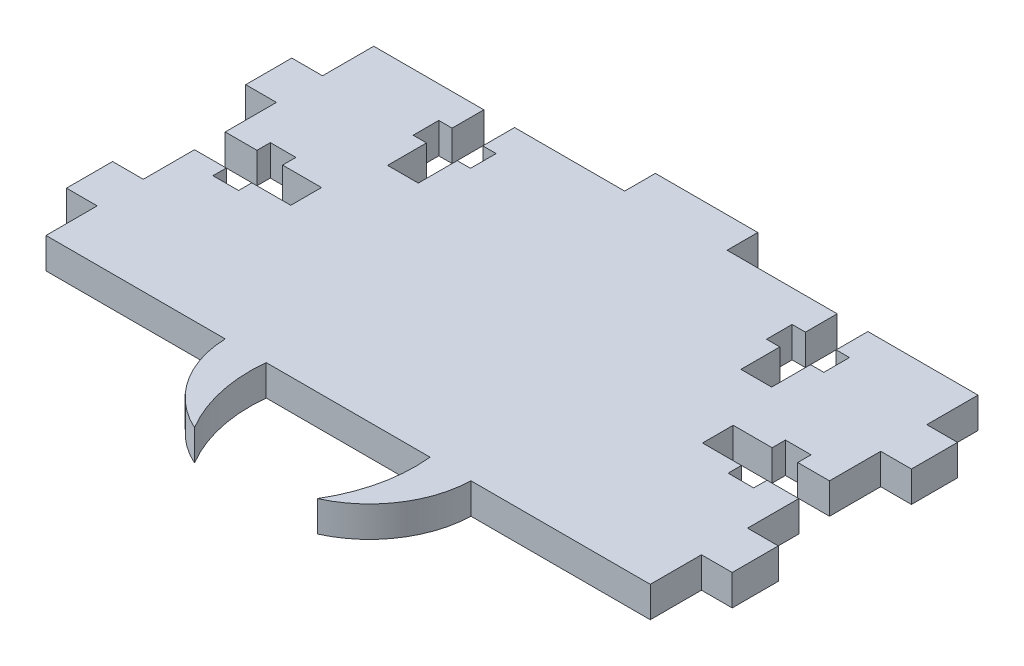
SolidWorks part; units mm, degrees
ref_plane "Front Plane" through (0, 0, 0) normal (0, 0, 1) x (1, 0, 0)
ref_plane "Top Plane" through (0, 0, 0) normal (0, 1, 0) x (1, 0, 0)
ref_plane "Right Plane" through (0, 0, 0) normal (1, 0, 0) x (0, 0, -1)
sketch "Sketch1" plane through (0, 0, 0) normal (0, 1, 0) x (1, 0, 0)
  line L0 (0, 27) -> (3, 27)
  line L1 (0, 0) -> (-17.5, 0)
  line L2 (0, 0) -> (0, 5)
  line L3 (0, 32) -> (-10.75, 32)
  line L4 (-59, 0) -> (-59, 5)
  line L5 (0, 17.5) -> (-3.1, 17.5)
  line L6 (-3.1, 17.5) -> (-3.1, 18.8)
  line L7 (-3.1, 18.8) -> (-5.6, 18.8)
  line L8 (-5.6, 18.8) -> (-5.6, 17.5)
  line L9 (-5.6, 17.5) -> (-9.4, 17.5)
  line L10 (-9.4, 17.5) -> (-9.4, 14.5)
  line L11 (-9.4, 14.5) -> (-5.6, 14.5)
  line L12 (-5.6, 14.5) -> (-5.6, 13.2)
  line L13 (-5.6, 13.2) -> (-3.1, 13.2)
  line L14 (-3.1, 13.2) -> (-3.1, 14.5)
  line L15 (-3.1, 14.5) -> (0, 14.5)
  line L16 (0, 17.5) -> (0, 22.5)
  line L17 (3, 27) -> (3, 22.5)
  line L18 (3, 22.5) -> (0, 22.5)
  line L19 (0, 27) -> (0, 32)
  line L20 (-49.6, 16) -> (-9.4, 16) construction
  line L21 (-29.5, 35) -> (-29.5, 0) construction
  line L22 (3, 9.5) -> (0, 9.5)
  line L23 (0, 5) -> (3, 5)
  line L24 (3, 5) -> (3, 9.5)
  line L25 (0, 9.5) -> (0, 14.5)
  line L26 (-55.9, 13.2) -> (-55.9, 14.5)
  line L27 (-53.4, 14.5) -> (-53.4, 13.2)
  line L28 (-55.9, 17.5) -> (-55.9, 18.8)
  line L29 (-53.4, 18.8) -> (-53.4, 17.5)
  line L30 (-55.9, 18.8) -> (-53.4, 18.8)
  line L31 (-53.4, 13.2) -> (-55.9, 13.2)
  line L32 (-49.6, 17.5) -> (-49.6, 14.5)
  line L33 (-49.6, 14.5) -> (-53.4, 14.5)
  line L34 (-53.4, 17.5) -> (-49.6, 17.5)
  line L35 (-59, 17.5) -> (-55.9, 17.5)
  line L36 (-55.9, 14.5) -> (-59, 14.5)
  line L37 (-59, 5) -> (-62, 5)
  line L38 (-62, 5) -> (-62, 9.5)
  line L39 (-62, 9.5) -> (-59, 9.5)
  line L40 (-59, 27) -> (-62, 27)
  line L41 (-62, 27) -> (-62, 22.5)
  line L42 (-62, 22.5) -> (-59, 22.5)
  line L43 (-59, 17.5) -> (-59, 22.5)
  line L44 (-59, 27) -> (-59, 32)
  line L45 (-59, 9.5) -> (-59, 14.5)
  line L46 (-21.5, 0) -> (-37.5, 0)
  line L47 (-41.5, 0) -> (-59, 0)
  line L48 (-48.25, 32) -> (-48.25, 28.9)
  line L49 (-24.5, 32) -> (-24.5, 35)
  line L50 (-24.5, 35) -> (-34.5, 35)
  line L51 (-34.5, 35) -> (-34.5, 32)
  line L52 (-34.5, 32) -> (-45.25, 32)
  line L53 (-48.25, 28.9) -> (-49.55, 28.9)
  line L54 (-49.55, 28.9) -> (-49.55, 26.4)
  line L55 (-49.55, 26.4) -> (-48.25, 26.4)
  line L56 (-48.25, 26.4) -> (-48.25, 22.6)
  line L57 (-48.25, 22.6) -> (-45.25, 22.6)
  line L58 (-45.25, 22.6) -> (-45.25, 26.4)
  line L59 (-45.25, 26.4) -> (-43.95, 26.4)
  line L60 (-43.95, 26.4) -> (-43.95, 28.9)
  line L61 (-43.95, 28.9) -> (-45.25, 28.9)
  line L62 (-45.25, 28.9) -> (-45.25, 32)
  line L63 (-48.25, 32) -> (-59, 32)
  line L64 (-10.75, 22.6) -> (-13.75, 22.6)
  line L65 (-10.75, 26.4) -> (-10.75, 22.6)
  line L66 (-15.05, 28.9) -> (-13.75, 28.9)
  line L67 (-10.75, 28.9) -> (-9.45, 28.9)
  line L68 (-9.45, 26.4) -> (-10.75, 26.4)
  line L69 (-9.45, 28.9) -> (-9.45, 26.4)
  line L70 (-10.75, 32) -> (-10.75, 28.9)
  line L71 (-13.75, 28.9) -> (-13.75, 32)
  line L72 (-15.05, 26.4) -> (-15.05, 28.9)
  line L73 (-13.75, 26.4) -> (-15.05, 26.4)
  line L74 (-13.75, 22.6) -> (-13.75, 26.4)
  line L75 (-13.75, 32) -> (-24.5, 32)
  arc A0 (-21.5, 0) -> (-23.5, -9) centre (-35.9728, -1.506) cw
  arc A1 (-17.5, 0) -> (-23.5, -9) centre (-27.7534, 0.3356) cw
  arc A2 (-37.5, 0) -> (-35.5, -9) centre (-23.0272, -1.506) ccw
  arc A3 (-41.5, 0) -> (-35.5, -9) centre (-31.2466, 0.3356) ccw
  point P5 (0, 27)
  point P22 (-17.5, 0)
  point P24 (-48.25, 32)
  point P30 (-23.5, -9)
  point P52 (-21.5, 0)
  point P81 (0, 0)
  point P82 (0, 0)
  point P83 (-43.95, 27.65)
  point P94 (-15.05, 27.65)
  dimension "D15" = 10.2589
  dimension "D16" = 14.551
  dimension "D1" = 32
  dimension "D2" = 59
  dimension "D3" = 3.1
  dimension "D4" = 2.5
  dimension "D5" = 3.8
  dimension "D6" = 3
  dimension "D7" = 1.3
  dimension "D8" = 5
  dimension "D9" = 4.5
  dimension "D10" = 3
  dimension "D11" = 10
  dimension "D12" = 4
  dimension "D13" = 2
  dimension "D14" = 9
  dimension "D17" = 17.5
  dimension "D18" = 10.75
extrude "Boss-Extrude1" add sketch "Sketch1" along normal blind 3
